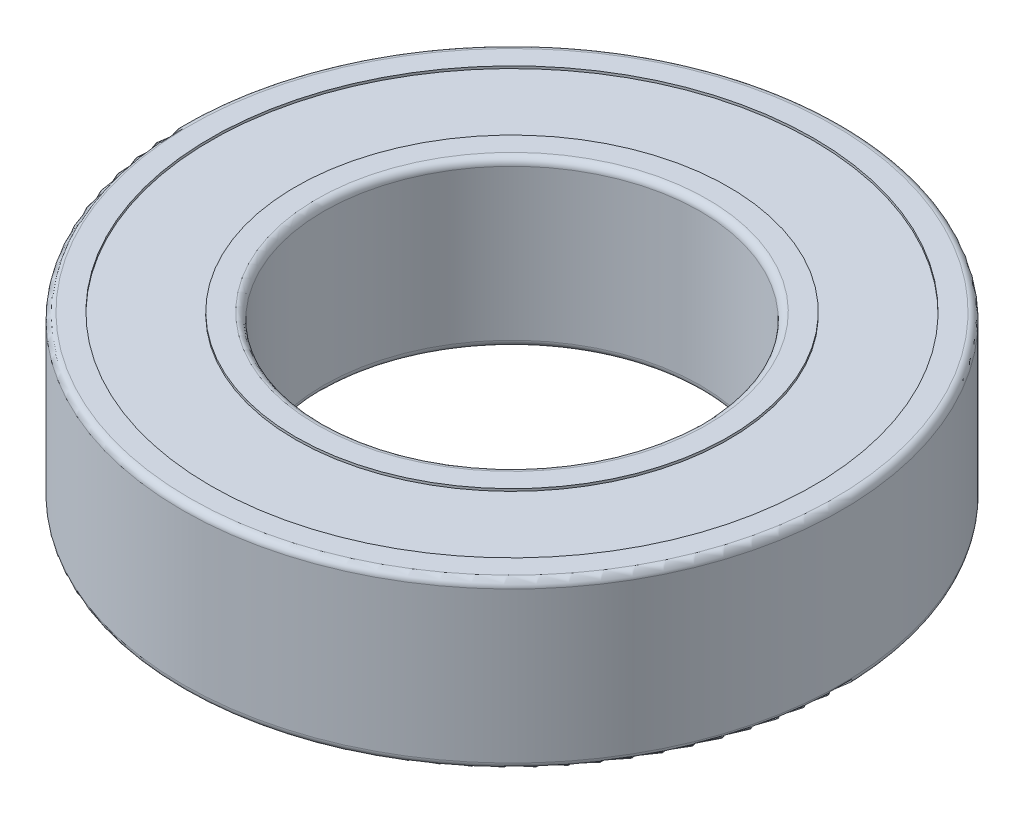
SolidWorks part; units mm, degrees
ref_plane "Alzado" through (0, 0, 0) normal (0, 0, 1) x (1, 0, 0)
ref_plane "Planta" through (0, 0, 0) normal (0, 1, 0) x (1, 0, 0)
ref_plane "Vista lateral" through (0, 0, 0) normal (1, 0, 0) x (0, 0, -1)
sketch "Croquis1" plane through (0, 0, 0) normal (0, 1, 0) x (1, 0, 0)
  circle A0 centre (0, 0) radius 8
  circle A1 centre (0, 0) radius 14
  dimension "D1" = 28
  dimension "D2" = 16
extrude "Saliente-Extruir1" add sketch "Croquis1" along normal blind 7
sketch "Croquis2" plane through (0, 7, 0) normal (0, 1, 0) x (1, 0, 0)
  circle A0 centre (0, 0) radius 12.8
  circle A1 centre (0, 0) radius 9.2
  circle A2 centre (0, 0) radius 8 construction
  circle A3 centre (0, 0) radius 14 construction
  dimension "D1" = 1.2
  dimension "D2" = 1.2
extrude "Cortar-Extruir1" cut sketch "Croquis2" against normal blind 0.1
ref_plane "Plano1" through (0, 3.5, 0) normal (0, 1, 0) x (1, 0, 0)
mirror "Simetría1" about plane through (0, 3.5, 0) normal (0, 1, 0) of "Cortar-Extruir1"
fillet "Redondeo1" radius 0.3 4 edges at (0, 0, 14) (0, 7, 14) (0, 0, 8) (0, 7, 8)
